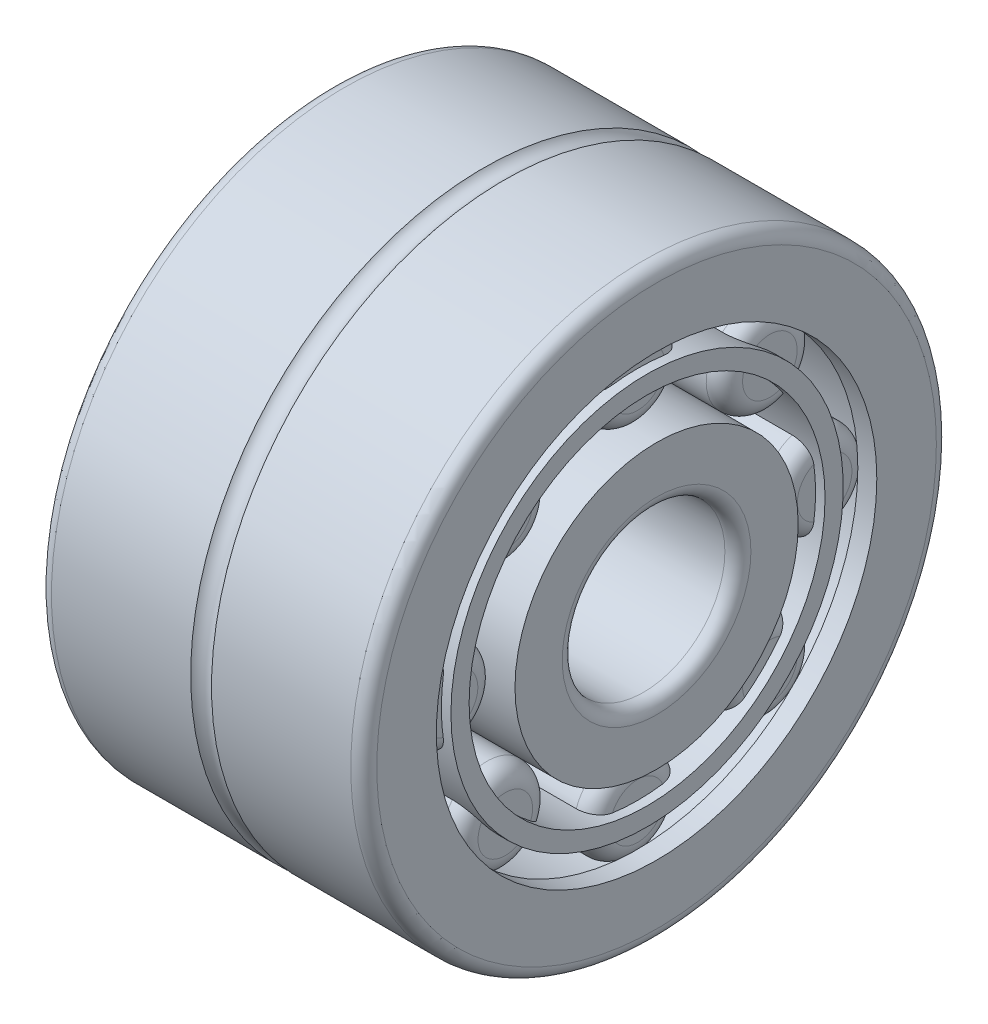
SolidWorks part; units mm, degrees
ref_plane "Plane1" through (0, 0, 0) normal (0, 0, 1) x (1, 0, 0)
ref_plane "Plane2" through (0, 0, 0) normal (0, 1, 0) x (1, 0, 0)
ref_plane "Plane3" through (0, 0, 0) normal (1, 0, 0) x (0, 0, -1)
sketch "Clipboard" plane through (0, 0, 0) normal (0, 0, 1) x (1, 0, 0)
  line L0 (-10, 0) -> (10, 0) construction
  line L1 (0, 0) -> (27.3694, -3.8465)
  line L2 (0, 0) -> (36.1572, 5.0816)
  line L3 (0, 0) -> (44.9449, -6.3166)
  line L4 (0, 0) -> (-22.3471, -0.7804)
  dimension "Race_OD" = 45.3866
  dimension "CLdia" = 36.5125
  dimension "Count" = 8
  dimension "Show_count" = 8
  dimension "Max_count" = 8
  dimension "Min_count" = 2
  dimension "Race_ID" = 27.6384
sketch "OutRacSke" plane through (0, 0, 0) normal (0, 0, 1) x (1, 0, 0)
  line L0 (-14.0229, 22.6933) -> (-14.0229, 21.4933)
  line L1 (-14.0229, 21.4933) -> (-15.875, 21.4933)
  line L2 (-15.875, 21.4933) -> (-15.875, 27.305)
  line L3 (-14.605, 28.575) -> (-1.016, 28.575)
  line L4 (15.875, 27.305) -> (15.875, 21.4933)
  line L5 (15.875, 21.4933) -> (14.0229, 21.4933)
  line L6 (14.0229, 21.4933) -> (14.0229, 22.6933)
  line L7 (14.0229, 22.6933) -> (-14.0229, 22.6933)
  line L8 (-7.9375, 0) -> (7.9375, 0) construction
  line L9 (1.016, 28.575) -> (14.605, 28.575)
  arc A0 (-15.875, 27.305) -> (-14.605, 28.575) centre (-14.605, 27.305) cw
  arc A1 (14.605, 28.575) -> (15.875, 27.305) centre (14.605, 27.305) cw
  arc A2 (-1.016, 28.575) -> (1.016, 28.575) centre (0, 29.337) ccw
  dimension "Radius" = 1.27
  dimension "OD" = 57.15
  dimension "Cyl_Len" = 28.0458
  dimension "Width" = 31.75
  dimension "halfWidth" = 15.875
  dimension "D1" = 14.0229
  dimension "Groove_Dp" = 1.2
  dimension "Race_OD" = 45.3866
  dimension "D2" = 0.762
revolve "OuterRace" add sketch "OutRacSke" angle 360 about L8
sketch "RolDetSke" plane through (0, 0, 0) normal (0, 0, 1) x (1, 0, 0)
  line L0 (-14.0229, 20.9188) -> (-14.0229, 18.2562)
  line L1 (-14.0229, 18.2562) -> (14.0229, 18.2562)
  line L2 (14.0229, 18.2562) -> (14.0229, 20.9188)
  line L3 (12.2479, 22.6938) -> (-12.2479, 22.6938)
  line L4 (-28.575, 18.2562) -> (28.575, 18.2562) construction
  arc A0 (14.0229, 20.9188) -> (12.2479, 22.6938) centre (12.2479, 20.9188) ccw
  arc A1 (-12.2479, 22.6938) -> (-14.0229, 20.9188) centre (-12.2479, 20.9188) ccw
  dimension "Cyl_Len" = 28.0458
  dimension "radius" = 1.775
  dimension "CLRad" = 18.2562
  dimension "Roller_diameter" = 8.8751
  dimension "halfCylLen" = 14.0229
revolve "RollerDetailed" add sketch "RolDetSke" angle 360 about L4
ref_axis "Axis1" through (-50, 0, 0) along (1, 0, 0)
sketch "RolSimSke" plane through (0, 25.4, 0) normal (0, 0, 1) x (1, 0, 0)
  line L0 (-14.0229, -4.4807) -> (-14.0229, -9.8058)
  line L1 (-25.4, -25.4) -> (25.4, -25.4) construction
  line L2 (14.0229, -9.8058) -> (14.0229, -4.4807)
  line L3 (12.2479, -2.7057) -> (-12.2479, -2.7057)
  line L5 (12.2479, -11.5808) -> (-12.2479, -11.5808)
  arc A0 (14.0229, -4.4807) -> (12.2479, -2.7057) centre (12.2479, -4.4807) ccw
  arc A1 (-12.2479, -2.7057) -> (-14.0229, -4.4807) centre (-12.2479, -4.4807) ccw
  arc A2 (14.0229, -9.8058) -> (12.2479, -11.5808) centre (12.2479, -9.8058) cw
  arc A3 (-12.2479, -11.5808) -> (-14.0229, -9.8058) centre (-12.2479, -9.8058) cw
  dimension "radius" = 1.775
  dimension "Roller_diameter" = 8.8751
  dimension "Bore" = 27.6384
  dimension "Cyl_Len" = 28.0458
  dimension "halfLength" = 14.0229
revolve "RollersSimplified" [suppressed] add sketch "RolSimSke" angle 360 about L1
sketch "InsRacSke" plane through (0, 0, 0) normal (0, 0, 1) x (1, 0, 0)
  line L2 (-15.875, 13.8192) -> (-15.875, 9.2075)
  line L4 (-14.605, 7.9375) -> (14.605, 7.9375)
  line L5 (15.875, 9.2075) -> (15.875, 13.8192)
  line L8 (15.875, 13.8192) -> (-15.875, 13.8192)
  line L9 (-7.9375, 0) -> (7.9375, 0) construction
  arc A0 (-15.875, 9.2075) -> (-14.605, 7.9375) centre (-14.605, 9.2075) ccw
  arc A2 (14.605, 7.9375) -> (15.875, 9.2075) centre (14.605, 9.2075) ccw
  dimension "halfWidth" = 15.875
  dimension "Race_ID" = 27.6384
  dimension "radius" = 1.27
  dimension "Bore" = 15.875
  dimension "Width_IR" = 31.75
revolve "InnerRace" add sketch "InsRacSke" angle 360 about L9
sketch "CagSpiSke" plane through (0, 0, 0) normal (0, 0, 1) x (1, 0, 0)
  line L0 (-17.1595, 0) -> (17.1595, 0) construction
  line L3 (-14.949, 17.3687) -> (14.949, 17.3687)
  line L4 (-14.949, 17.3687) -> (-14.949, 19.1438)
  line L5 (-14.949, 19.1438) -> (14.949, 19.1438)
  line L6 (14.949, 17.3687) -> (14.949, 19.1438)
  dimension "d2" = 34.7375
  dimension "cage_width" = 29.8979
  dimension "halfwidth" = 14.949
  dimension "cage_thickness" = 1.775
revolve "CageSpine" add sketch "CagSpiSke" angle 360 about L0
pattern_circular "RollersDetailed" count 8 every 45 about axis through (-50, 0, 0) along (1, 0, 0) of "RollerDetailed"
equation "\"halfWidth@OutRacSke\" =  \"Width@OutRacSke\" / 2"
equation "\"CLdia@Clipboard\" =  ( \"Race_OD@Clipboard\" + \"Race_ID@Clipboard\" )  / 2"
equation "\"CLRad@RolDetSke\" = ( \"Race_OD@Clipboard\" + \"Race_ID@Clipboard\" )  / 4"
equation "\"Roller_diameter@RolDetSke\" =  ( \"Race_OD@Clipboard\" -  \"Race_ID@Clipboard\" )  / 2 + .001"
equation "\"Roller_diameter@RolSimSke\" = ( \"Race_OD@Clipboard\" -  \"Race_ID@Clipboard\" )  / 2 + .001"
equation "\"radius@RolDetSke\" = \"Roller_diameter@RolDetSke\" / 5"
equation "\"radius@RolSimSke\" = \"Roller_diameter@RolSimSke\" / 5"
equation "\"Cyl_Len@OutRacSke\" = \"Cyl_Len@RolDetSke\""
equation "\"Cyl_Len@RolSimSke\" = \"Cyl_Len@RolDetSke\""
equation "\"halfCylLen@RolDetSke\" = \"Cyl_Len@RolDetSke\" / 2"
equation "\"D1@OutRacSke\" = \"Cyl_Len@OutRacSke\" / 2"
equation "\"D2@OutRacSke\" = \"Radius@OutRacSke\" * .6"
equation "\"cage_width@CagSpiSke\" =  ( \"Cyl_Len@RolDetSke\" + \"Width@OutRacSke\" )  / 2"
equation "\"halfwidth@CagSpiSke\" = \"cage_width@CagSpiSke\" / 2"
equation "\"cage_thickness@CagSpiSke\" = \"Roller_diameter@RolDetSke\" / 5"
equation "\"d2@CagSpiSke\" = \"CLRad@RolDetSke\" * 2 - \"cage_thickness@CagSpiSke\""
equation "\"Max_count@Clipboard\" = int( 3.14159265 / atn(( \"Roller_diameter@RolDetSke\" / 2) / sqr( \"CLRad@RolDetSke\"  *  \"CLRad@RolDetSke\" - ( \"Roller_diameter@RolDetSke\" / 2) *  ( \"Roller_diameter@RolDetSke\" / 2))))"
equation "\"Max_count@Clipboard\" = ((sgn( \"Max_count@Clipboard\" - \"Count@Clipboard\" )-1)*( \"Max_count@Clipboard\" - \"Count@Clipboard\" ))/-2+ \"Count@Clipboard\""
equation "\"Count@RollersDetailed\" = int( \"Show_count@Clipboard\" ) "
equation "\"Count@RollersDetailed\" = ((sgn( \"Count@RollersDetailed\" - \"Max_count@Clipboard\" )-1)*( \"Count@RollersDetailed\" - \"Max_count@Clipboard\" ))/-2+ \"Max_count@Clipboard\""
equation "\"Count@RollersDetailed\" = ((sgn( \"Count@RollersDetailed\" - \"Min_count@Clipboard\" )+1)*( \"Count@RollersDetailed\" - \"Min_count@Clipboard\"))/2 +\"Min_count@Clipboard\""
equation "\"Angle@RollersDetailed\" = 360.0 / \"Max_count@Clipboard\""
equation "\"Bore@RolSimSke\" = \"Race_ID@Clipboard\""
equation "\"Race_ID@InsRacSke\" = \"Race_ID@Clipboard\""
equation "\"halfWidth@InsRacSke\" = \"Width_IR@InsRacSke\" / 2"
equation "\"halfLength@RolSimSke\" = \"Cyl_Len@RolSimSke\" / 2"
equation "\"Race_OD@OutRacSke\" = \"Race_OD@Clipboard\""
equation "\"Width_IR@InsRacSke\" = \"Width@OutRacSke\""
equation "\"Angle@CageSpine\" =  \"Angle@RollersDetailed\" * ( \"Count@RollersDetailed\" -1 + int( \"Count@RollersDetailed\" / \"Max_count@Clipboard\" ) )  + 0.001 -  int( \"Count@RollersDetailed\" / \"Max_count@Clipboard\" ) * 0.001"
equation "\"Angle@CageSpine\" =  \"Angle@CageSpine\" * int( \"Min_count@Clipboard\" / 2) + int(1 / \"Min_count@Clipboard\")  * 0.001"
equation "\"radius@InsRacSke\" = \"Radius@OutRacSke\""
